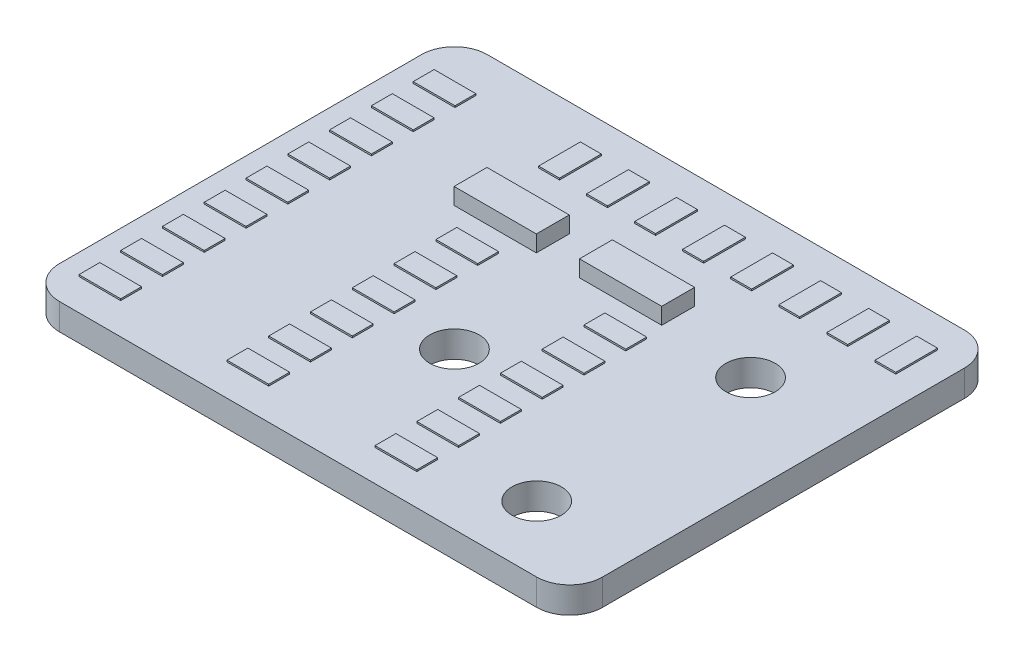
SolidWorks part; units mm, degrees
ref_plane "Front Plane" through (0, 0, 0) normal (0, 0, 1) x (1, 0, 0)
ref_plane "Top Plane" through (0, 0, 0) normal (0, 1, 0) x (1, 0, 0)
ref_plane "Right Plane" through (0, 0, 0) normal (1, 0, 0) x (0, 0, -1)
sketch "Sketch1" plane through (0, 0, 0) normal (0, 1, 0) x (1, 0, 0)
  line L1 (14.5, 13) -> (-14.5, 13)
  line L2 (16.5, 11) -> (16.5, -11)
  line L3 (14.5, -13) -> (-14.5, -13)
  line L4 (-16.5, 11) -> (-16.5, -11)
  line L5 (16.5, 13) -> (-16.5, -13) construction
  line L6 (16.5, -13) -> (-16.5, 13) construction
  circle A0 centre (0, -3.5) radius 1.5
  circle A1 centre (10.5, 4) radius 1.5
  circle A2 centre (10.5, -9) radius 1.5
  arc A3 (14.5, 13) -> (16.5, 11) centre (14.5, 11) cw
  arc A4 (16.5, -11) -> (14.5, -13) centre (14.5, -11) cw
  arc A5 (-14.5, -13) -> (-16.5, -11) centre (-14.5, -11) cw
  arc A6 (-14.5, 13) -> (-16.5, 11) centre (-14.5, 11) ccw
  point P0 (0, 0)
  point P12 (0, 0)
  dimension "D3" = 3
  dimension "D7" = 4
  dimension "D9" = 2
  dimension "D1" = 26
  dimension "D2" = 33
  dimension "D4" = 16.5
  dimension "D5" = 9.5
  dimension "D6" = 27
  dimension "D8" = 17
extrude "Boss-Extrude1" add sketch "Sketch1" along normal blind 1.6
sketch "Sketch2" plane through (0, 1.6, 0) normal (0, 1, 0) x (1, 0, 0)
  line L0 (-16.5, 11) -> (-16.5, -11) construction
  line L5 (-15.23, 10.495) -> (-12.69, 10.495)
  line L6 (-15.23, 10.495) -> (-15.23, 9.225)
  line L11 (-15.23, 9.225) -> (-12.69, 9.225)
  line L12 (-12.69, 10.495) -> (-12.69, 9.225)
  line L17 (-15.23, 10.495) -> (-12.69, 9.225) construction
  line L18 (-15.23, 9.225) -> (-12.69, 10.495) construction
  line L23 (-6.975, 11.13) -> (-5.705, 11.13)
  line L24 (-6.975, 11.13) -> (-6.975, 8.59)
  line L29 (-6.975, 8.59) -> (-5.705, 8.59)
  line L30 (-5.705, 11.13) -> (-5.705, 8.59)
  line L35 (-6.975, 11.13) -> (-5.705, 8.59) construction
  line L36 (-6.975, 8.59) -> (-5.705, 11.13) construction
  line L53 (-14.5, -13) -> (14.5, -13) construction
  line L54 (-15.23, 6.685) -> (-12.69, 6.685)
  line L71 (-12.69, 7.955) -> (-12.69, 6.685)
  line L72 (-15.23, 7.955) -> (-12.69, 7.955)
  line L77 (-15.23, 7.955) -> (-15.23, 6.685)
  line L78 (-15.23, 4.145) -> (-12.69, 4.145)
  line L79 (-12.69, 5.415) -> (-12.69, 4.145)
  line L80 (-15.23, 5.415) -> (-12.69, 5.415)
  line L81 (-15.23, 5.415) -> (-15.23, 4.145)
  line L82 (-15.23, 1.605) -> (-12.69, 1.605)
  line L83 (-12.69, 2.875) -> (-12.69, 1.605)
  line L84 (-15.23, 2.875) -> (-12.69, 2.875)
  line L85 (-15.23, 2.875) -> (-15.23, 1.605)
  line L86 (-15.23, -0.935) -> (-12.69, -0.935)
  line L87 (-12.69, 0.335) -> (-12.69, -0.935)
  line L88 (-15.23, 0.335) -> (-12.69, 0.335)
  line L89 (-15.23, 0.335) -> (-15.23, -0.935)
  line L90 (-15.23, -3.475) -> (-12.69, -3.475)
  line L91 (-12.69, -2.205) -> (-12.69, -3.475)
  line L92 (-15.23, -2.205) -> (-12.69, -2.205)
  line L93 (-15.23, -2.205) -> (-15.23, -3.475)
  line L94 (-15.23, -6.015) -> (-12.69, -6.015)
  line L95 (-12.69, -4.745) -> (-12.69, -6.015)
  line L96 (-15.23, -4.745) -> (-12.69, -4.745)
  line L97 (-15.23, -4.745) -> (-15.23, -6.015)
  line L98 (-15.23, -8.555) -> (-12.69, -8.555)
  line L99 (-12.69, -7.285) -> (-12.69, -8.555)
  line L100 (-15.23, -7.285) -> (-12.69, -7.285)
  line L101 (-15.23, -7.285) -> (-15.23, -8.555)
  line L102 (-15.23, -11.095) -> (-12.69, -11.095)
  line L103 (-12.69, -9.825) -> (-12.69, -11.095)
  line L104 (-15.23, -9.825) -> (-12.69, -9.825)
  line L105 (-15.23, -9.825) -> (-15.23, -11.095)
  line L106 (-6.23, 6.685) -> (-3.69, 6.685) [skipped]
  line L107 (-3.69, 7.955) -> (-3.69, 6.685) [skipped]
  line L108 (-6.23, 7.955) -> (-3.69, 7.955) [skipped]
  line L109 (-6.23, 7.955) -> (-6.23, 6.685) [skipped]
  line L110 (-6.23, 4.145) -> (-3.69, 4.145) [skipped]
  line L111 (-3.69, 5.415) -> (-3.69, 4.145) [skipped]
  line L112 (-6.23, 5.415) -> (-3.69, 5.415) [skipped]
  line L113 (-6.23, 5.415) -> (-6.23, 4.145) [skipped]
  line L114 (-6.23, 1.605) -> (-3.69, 1.605)
  line L115 (-3.69, 2.875) -> (-3.69, 1.605)
  line L116 (-6.23, 2.875) -> (-3.69, 2.875)
  line L117 (-6.23, 2.875) -> (-6.23, 1.605)
  line L118 (-6.23, -0.935) -> (-3.69, -0.935)
  line L119 (-3.69, 0.335) -> (-3.69, -0.935)
  line L120 (-6.23, 0.335) -> (-3.69, 0.335)
  line L121 (-6.23, 0.335) -> (-6.23, -0.935)
  line L122 (-6.23, -3.475) -> (-3.69, -3.475)
  line L123 (-3.69, -2.205) -> (-3.69, -3.475)
  line L124 (-6.23, -2.205) -> (-3.69, -2.205)
  line L125 (-6.23, -2.205) -> (-6.23, -3.475)
  line L126 (-6.23, -6.015) -> (-3.69, -6.015)
  line L127 (-3.69, -4.745) -> (-3.69, -6.015)
  line L128 (-6.23, -4.745) -> (-3.69, -4.745)
  line L129 (-6.23, -4.745) -> (-6.23, -6.015)
  line L130 (-6.23, -8.555) -> (-3.69, -8.555)
  line L131 (-3.69, -7.285) -> (-3.69, -8.555)
  line L132 (-6.23, -7.285) -> (-3.69, -7.285)
  line L133 (-6.23, -7.285) -> (-6.23, -8.555)
  line L134 (-6.23, -11.095) -> (-3.69, -11.095)
  line L135 (-3.69, -9.825) -> (-3.69, -11.095)
  line L136 (-6.23, -9.825) -> (-3.69, -9.825)
  line L137 (-6.23, -9.825) -> (-6.23, -11.095)
  line L138 (2.77, 6.685) -> (5.31, 6.685) [skipped]
  line L139 (5.31, 7.955) -> (5.31, 6.685) [skipped]
  line L140 (2.77, 7.955) -> (5.31, 7.955) [skipped]
  line L141 (2.77, 7.955) -> (2.77, 6.685) [skipped]
  line L142 (2.77, 4.145) -> (5.31, 4.145) [skipped]
  line L143 (5.31, 5.415) -> (5.31, 4.145) [skipped]
  line L144 (2.77, 5.415) -> (5.31, 5.415) [skipped]
  line L145 (2.77, 5.415) -> (2.77, 4.145) [skipped]
  line L146 (2.77, 1.605) -> (5.31, 1.605)
  line L147 (5.31, 2.875) -> (5.31, 1.605)
  line L148 (2.77, 2.875) -> (5.31, 2.875)
  line L149 (2.77, 2.875) -> (2.77, 1.605)
  line L150 (2.77, -0.935) -> (5.31, -0.935)
  line L151 (5.31, 0.335) -> (5.31, -0.935)
  line L152 (2.77, 0.335) -> (5.31, 0.335)
  line L153 (2.77, 0.335) -> (2.77, -0.935)
  line L154 (2.77, -3.475) -> (5.31, -3.475)
  line L155 (5.31, -2.205) -> (5.31, -3.475)
  line L156 (2.77, -2.205) -> (5.31, -2.205)
  line L157 (2.77, -2.205) -> (2.77, -3.475)
  line L158 (2.77, -6.015) -> (5.31, -6.015)
  line L159 (5.31, -4.745) -> (5.31, -6.015)
  line L160 (2.77, -4.745) -> (5.31, -4.745)
  line L161 (2.77, -4.745) -> (2.77, -6.015)
  line L162 (2.77, -8.555) -> (5.31, -8.555)
  line L163 (5.31, -7.285) -> (5.31, -8.555)
  line L164 (2.77, -7.285) -> (5.31, -7.285)
  line L165 (2.77, -7.285) -> (2.77, -8.555)
  line L166 (2.77, -11.095) -> (5.31, -11.095)
  line L167 (5.31, -9.825) -> (5.31, -11.095)
  line L168 (2.77, -9.825) -> (5.31, -9.825)
  line L169 (2.77, -9.825) -> (2.77, -11.095)
  line L170 (-6.23, 9.225) -> (-3.69, 9.225) [skipped]
  line L171 (-3.69, 10.495) -> (-3.69, 9.225) [skipped]
  line L172 (-6.23, 10.495) -> (-3.69, 10.495) [skipped]
  line L173 (-6.23, 10.495) -> (-6.23, 9.225) [skipped]
  line L174 (2.77, 9.225) -> (5.31, 9.225) [skipped]
  line L175 (5.31, 10.495) -> (5.31, 9.225) [skipped]
  line L176 (2.77, 10.495) -> (5.31, 10.495) [skipped]
  line L177 (2.77, 10.495) -> (2.77, 9.225) [skipped]
  line L178 (-4.055, 11.13) -> (-2.785, 11.13)
  line L179 (-4.055, 11.13) -> (-4.055, 8.59)
  line L180 (-4.055, 8.59) -> (-2.785, 8.59)
  line L181 (-2.785, 11.13) -> (-2.785, 8.59)
  line L182 (-4.055, 11.13) -> (-2.785, 8.59) construction
  line L183 (-4.055, 8.59) -> (-2.785, 11.13) construction
  line L184 (-1.135, 11.13) -> (0.135, 11.13)
  line L185 (-1.135, 11.13) -> (-1.135, 8.59)
  line L186 (-1.135, 8.59) -> (0.135, 8.59)
  line L187 (0.135, 11.13) -> (0.135, 8.59)
  line L188 (-1.135, 11.13) -> (0.135, 8.59) construction
  line L189 (-1.135, 8.59) -> (0.135, 11.13) construction
  line L190 (1.785, 11.13) -> (3.055, 11.13)
  line L191 (1.785, 11.13) -> (1.785, 8.59)
  line L192 (1.785, 8.59) -> (3.055, 8.59)
  line L193 (3.055, 11.13) -> (3.055, 8.59)
  line L194 (1.785, 11.13) -> (3.055, 8.59) construction
  line L195 (1.785, 8.59) -> (3.055, 11.13) construction
  line L196 (4.705, 11.13) -> (5.975, 11.13)
  line L197 (4.705, 11.13) -> (4.705, 8.59)
  line L198 (4.705, 8.59) -> (5.975, 8.59)
  line L199 (5.975, 11.13) -> (5.975, 8.59)
  line L200 (4.705, 11.13) -> (5.975, 8.59) construction
  line L201 (4.705, 8.59) -> (5.975, 11.13) construction
  line L202 (7.625, 11.13) -> (8.895, 11.13)
  line L203 (7.625, 11.13) -> (7.625, 8.59)
  line L204 (7.625, 8.59) -> (8.895, 8.59)
  line L205 (8.895, 11.13) -> (8.895, 8.59)
  line L206 (7.625, 11.13) -> (8.895, 8.59) construction
  line L207 (7.625, 8.59) -> (8.895, 11.13) construction
  line L208 (10.545, 11.13) -> (11.815, 11.13)
  line L209 (10.545, 11.13) -> (10.545, 8.59)
  line L210 (10.545, 8.59) -> (11.815, 8.59)
  line L211 (11.815, 11.13) -> (11.815, 8.59)
  line L212 (10.545, 11.13) -> (11.815, 8.59) construction
  line L213 (10.545, 8.59) -> (11.815, 11.13) construction
  line L214 (13.465, 11.13) -> (14.735, 11.13)
  line L215 (13.465, 11.13) -> (13.465, 8.59)
  line L216 (13.465, 8.59) -> (14.735, 8.59)
  line L217 (14.735, 11.13) -> (14.735, 8.59)
  line L218 (13.465, 11.13) -> (14.735, 8.59) construction
  line L219 (13.465, 8.59) -> (14.735, 11.13) construction
  point P0 (-13.96, 9.86)
  point P5 (-6.34, 9.86)
  point P15 (-3.42, 9.86)
  point P124 (-0.5, 9.86)
  point P129 (2.42, 9.86)
  point P134 (5.34, 9.86)
  point P139 (8.26, 9.86)
  point P144 (11.18, 9.86)
  point P149 (14.1, 9.86)
  dimension "D1" = 1.27
  dimension "D2" = 2.54
  dimension "D3" = 2.54
  dimension "D4" = 22.86
  dimension "D5" = 10.16
  dimension "D6" = 22.86
  dimension "D7" = 9
  dimension "D8" = 3
  dimension "D9" = 8
extrude "Boss-Extrude2" add sketch "Sketch2" along normal blind 0.1
sketch "Sketch3" plane through (0, 1.6, 0) normal (0, 1, 0) x (1, 0, 0)
  line L0 (-14.5, -13) -> (14.5, -13) construction
  line L1 (-7.57, 6.05) -> (-2.57, 6.05)
  line L2 (-7.57, 6.05) -> (-7.57, 4.05)
  line L3 (-7.57, 4.05) -> (-2.57, 4.05)
  line L4 (-2.57, 6.05) -> (-2.57, 4.05)
  line L5 (-7.57, 6.05) -> (-2.57, 4.05) construction
  line L6 (-7.57, 4.05) -> (-2.57, 6.05) construction
  line L7 (0.05, 6.05) -> (5.05, 6.05)
  line L8 (0.05, 6.05) -> (0.05, 4.05)
  line L9 (0.05, 4.05) -> (5.05, 4.05)
  line L10 (5.05, 6.05) -> (5.05, 4.05)
  line L11 (0.05, 6.05) -> (5.05, 4.05) construction
  line L12 (0.05, 4.05) -> (5.05, 6.05) construction
  line L13 (-16.5, 11) -> (-16.5, -11) construction
  point P0 (-5.07, 5.05)
  point P5 (2.55, 5.05)
  dimension "D1" = 2
  dimension "D2" = 5
  dimension "D3" = 18.05
  dimension "D4" = 11.43
  dimension "D5" = 19.05
extrude "Boss-Extrude3" add sketch "Sketch3" along normal blind 1
